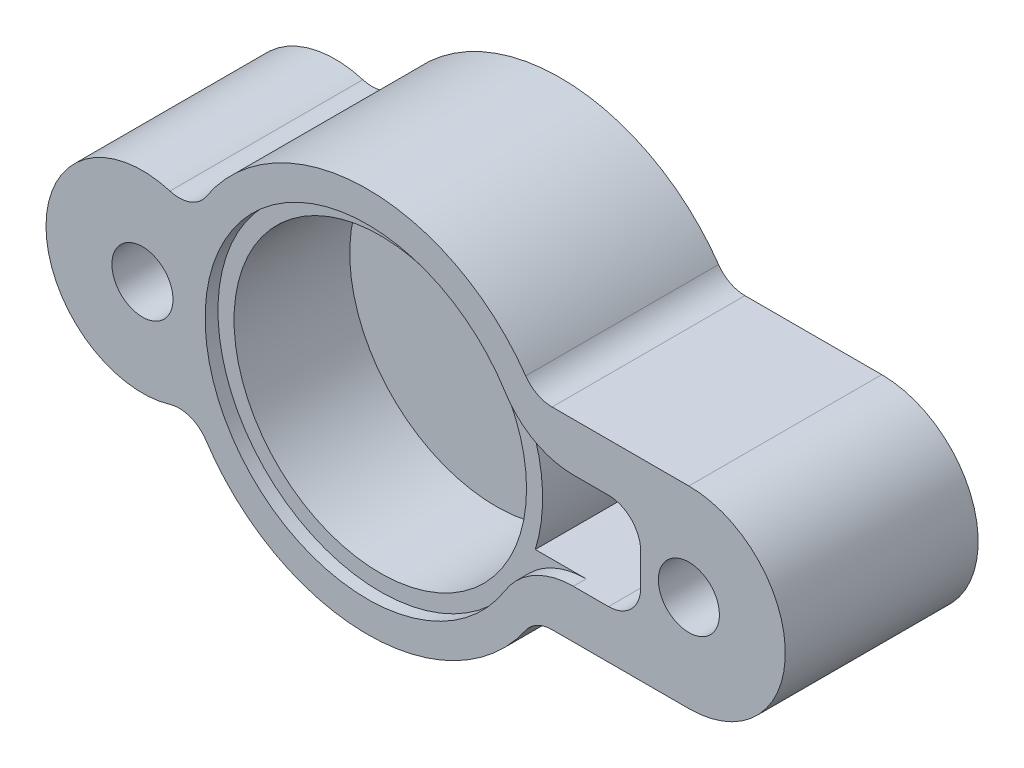
SolidWorks part; units mm, degrees
ref_plane "Plan de face" through (0, 0, 0) normal (0, 0, 1) x (1, 0, 0)
ref_plane "Plan de dessus" through (0, 0, 0) normal (0, 1, 0) x (1, 0, 0)
ref_plane "Plan de droite" through (0, 0, 0) normal (1, 0, 0) x (0, 0, -1)
sketch "Esquisse1" plane through (0, 0, 0) normal (0, 0, 1) x (1, 0, 0)
  line L0 (0, 0) -> (12, 0) construction
  line L1 (10.3923, 6) -> (20, 6)
  line L2 (20, 6) -> (20, -6)
  line L3 (20, -6) -> (10.3923, -6)
  circle A0 centre (0, 0) radius 9 construction
  circle A1 centre (0, 0) radius 12 construction
  arc A2 (10.3923, 6) -> (10.3923, -6) centre (0, 0) ccw
  point P10 (0, 0)
  dimension "D1" = 18
  dimension "D2" = 3
  dimension "D3" = 12
  dimension "D4" = 12
  dimension "D5" = 8
extrude "Boss.-Extru.1" add sketch "Esquisse1" along normal blind 12
sketch "Esquisse2" plane through (0, 0, 12) normal (0, 0, 1) x (1, 0, 0)
  circle A0 centre (0, 0) radius 9.1
  dimension "D1" = 18.2
extrude "Enlèv. mat.-Extru.3" cut sketch "Esquisse2" against normal blind 8
sketch "Esquisse3" plane through (0, 0, 12) normal (0, 0, 1) x (1, 0, 0)
  line L0 (9.6442, 3) -> (17, 3)
  line L1 (17, 3) -> (17, -3)
  line L2 (17, -3) -> (9.6442, -3)
  line L3 (20, 6) -> (10.3923, 6) construction
  line L4 (20, -6) -> (20, 6) construction
  line L5 (10.3923, -6) -> (20, -6) construction
  arc A0 (9.6442, 3) -> (9.6442, -3) centre (0, 0) cw
  circle A2 centre (0, 0) radius 9.1 construction
  dimension "D4" = 1
  dimension "D1" = 3
  dimension "D2" = 3
  dimension "D3" = 3
extrude "Enlèv. mat.-Extru.4" cut sketch "Esquisse3" against normal blind 6
sketch "Esquisse4" plane through (0, 0, 12) normal (0, 0, 1) x (1, 0, 0)
  line L0 (17, 3) -> (0, 3) construction
  line L1 (0, 3) -> (0, -3) construction
  line L2 (0, -3) -> (17, -3) construction
  line L3 (17, -3) -> (17, 3)
  line L4 (9.6442, 3) -> (17, 3)
  line L5 (17, -3) -> (9.6442, -3)
  arc A0 (9.6442, 3) -> (9.6442, -3) centre (0, 0) ccw
  arc A3 (9.6442, -3) -> (9.6442, 3) centre (0, 0) ccw construction
  point P6 (0, 0)
  point P11 (0, 0)
extrude "Enlèv. mat.-Extru.5" cut sketch "Esquisse4" against normal blind 0.8
sketch "Esquisse5" plane through (0, 0, 12) normal (0, 0, 1) x (1, 0, 0)
  line L0 (20, -6) -> (20, 6) construction
  line L1 (20, 6) -> (20, -6)
  line L2 (-10.8571, 5.111) -> (-10.8571, -5.111)
  arc A0 (20, 6) -> (20, -6) centre (20, 0) cw
  arc A1 (-10.8571, 5.111) -> (-10.8571, -5.111) centre (-14, 0) ccw
  arc A2 (10.3923, 6) -> (10.3923, -6) centre (0, 0) ccw construction
  point P8 (0, 0)
  point P14 (-13.7344, 0)
  point P16 (-12, 0)
  dimension "D1" = 2
extrude "Boss.-Extru.2" add sketch "Esquisse5" against normal up to vertex (12 mm away) up to point (10.3923, -6, 0)
sketch "Esquisse6" plane through (0, 0, 12) normal (0, 0, 1) x (1, 0, 0)
  circle A0 centre (-14, 0) radius 1.9
  circle A1 centre (20, 0) radius 1.9
  arc A2 (20, -6) -> (20, 6) centre (20, 0) ccw construction
  arc A3 (-10.8571, 5.111) -> (-10.8571, -5.111) centre (-14, 0) ccw construction
  dimension "D1" = 3.8
extrude "Enlèv. mat.-Extru.6" cut sketch "Esquisse6" against normal blind 10
fillet "Congé1" radius 5 2 edges at (9.6442, -3, 11.6) (9.6442, 3, 11.6)
fillet "Congé2" radius 2 6 edges at (17, -3, 9) (17, 3, 9) (10.3923, -6, 6) (10.3923, 6, 6) (-10.8571, 5.111, 6) (-10.8571, -5.111, 6)
